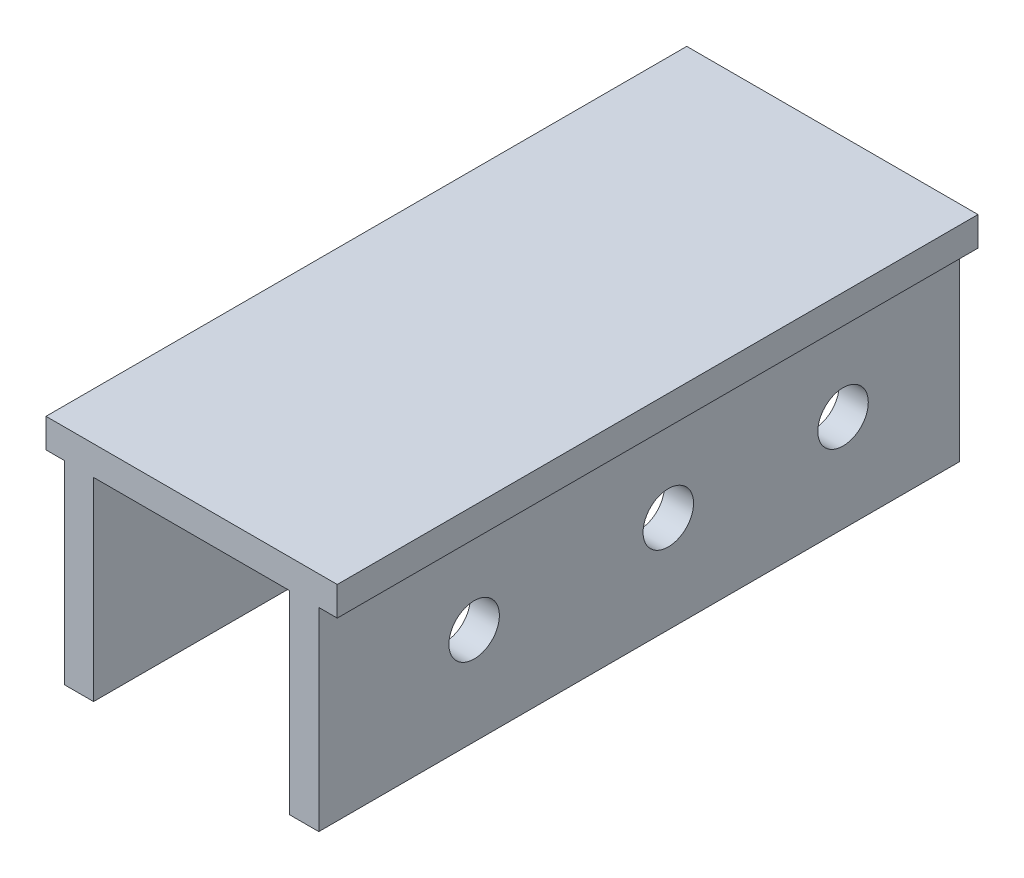
SolidWorks part; units mm, degrees
ref_plane "前视基准面" through (0, 0, 0) normal (0, 0, 1) x (1, 0, 0)
ref_plane "上视基准面" through (0, 0, 0) normal (0, 1, 0) x (1, 0, 0)
ref_plane "右视基准面" through (0, 0, 0) normal (1, 0, 0) x (0, 0, -1)
other "Configuration Table"
sketch "草图1" plane through (0, 0, 0) normal (0, 0, 1) x (1, 0, 0)
  line L0 (0, 16.7537) -> (0, -26.178) construction
  line L1 (-15, -1.5) -> (-13.1, -1.5)
  line L2 (-15, -1.5) -> (-15, 1.5)
  line L3 (-15, 1.5) -> (15, 1.5)
  line L4 (15, -1.5) -> (15, 1.5)
  line L5 (-15, -1.5) -> (15, 1.5) construction
  line L6 (-15, 1.5) -> (15, -1.5) construction
  line L7 (-10.1, -1.5) -> (10.1, -1.5)
  line L9 (-13.1, -1.5) -> (-13.1, -21.5)
  line L10 (-13.1, -21.5) -> (-10.1, -21.5)
  line L11 (-10.1, -1.5) -> (-10.1, -21.5)
  line L13 (10.1, -1.5) -> (10.1, -21.5)
  line L14 (10.1, -21.5) -> (13.1, -21.5)
  line L15 (13.1, -1.5) -> (13.1, -21.5)
  line L16 (13.1, -1.5) -> (15, -1.5)
  point P0 (0, 0)
  dimension "D1" = 3
  dimension "D2" = 30
  dimension "D3" = 20
  dimension "D4" = 3
  dimension "D5" = 20.2
extrude "凸台-拉伸1" add sketch "草图1" along normal blind 66
hole_wizard "孔1" positions "草图2" profile "草图3" legacy
sketch "草图2" plane through (13.1, 0, 0) normal (1, 0, 0) x (0, 0, -1)
  line L0 (-66, -1.5) -> (0, -1.5) construction
  line L5 (0, -21.5) -> (0, -1.5) construction
  point P0 (-50, -11.5)
  point P2 (-30, -11.5)
  point P4 (-12, -11.5)
  dimension "D1" = 10
  dimension "D2" = 12
  dimension "D3" = 20
  dimension "D4" = 18
sketch "草图3" plane through (13.1, -11.5, 50) normal (0, 1, 0) x (0, 0, -1)
  line L0 (0, 0) -> (0, 100)
  line L1 (0, 100) -> (2.6, 100)
  line L2 (2.6, 100) -> (2.6, 0)
  line L3 (2.6, 0) -> (0, 0)
  line L4 (0, 110) -> (0, -10) construction
  dimension "直径" = 5.2
  dimension "深度" = 100
